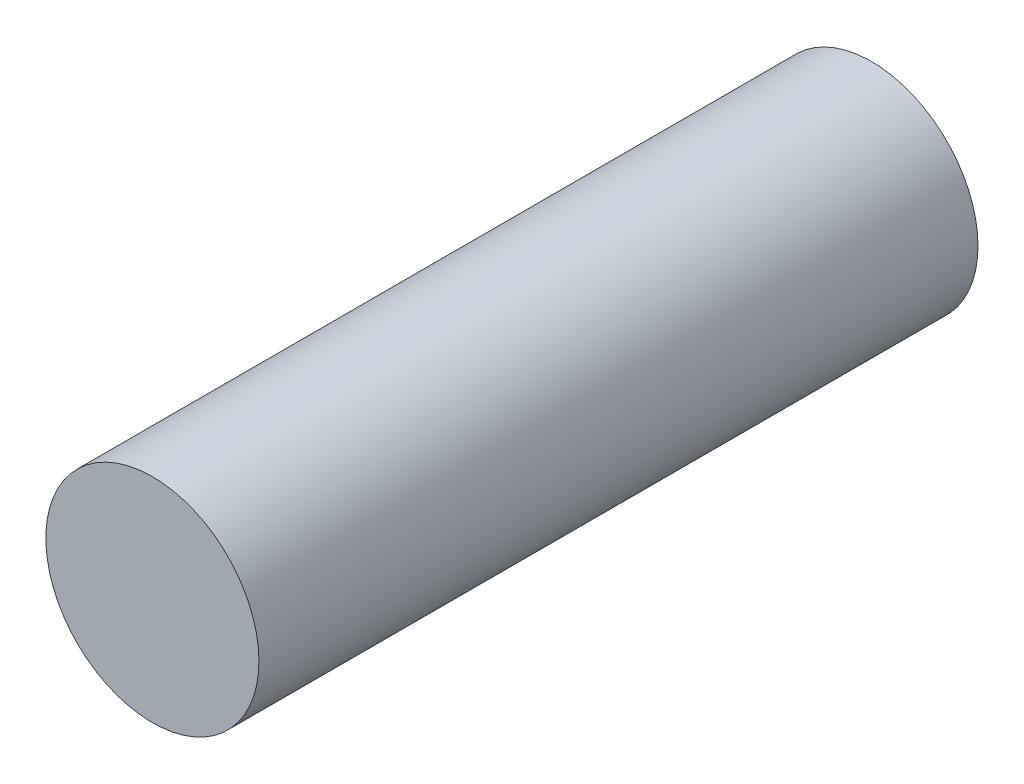
SolidWorks part; units mm, degrees
ref_plane "Front Plane" through (0, 0, 0) normal (0, 0, 1) x (1, 0, 0)
ref_plane "Top Plane" through (0, 0, 0) normal (0, 1, 0) x (1, 0, 0)
ref_plane "Right Plane" through (0, 0, 0) normal (1, 0, 0) x (0, 0, -1)
sketch "Sketch1" plane through (0, 0, 0) normal (0, 0, 1) x (1, 0, 0)
  circle A0 centre (0, 0) radius 4.445
  dimension "D1" = 8.89
extrude "L12_Shaft" add sketch "Sketch1" along normal blind 30
hole_wizard "Tap Drill for M8x1.25 Tap1" positions "Sketch3" profile "Sketch2" hole size "M8x1.25" standard "ANSI Metric"
sketch "Sketch3" plane through (0, 0, 0) normal (0, 0, -1) x (-1, 0, 0)
  point P0 (0, 0)
sketch "Sketch2" plane through (0, 0, 0) normal (1, 0, 0) x (0, 1, 0)
  line L0 (0, 0) -> (0, 11.5679)
  line L1 (0, 11.5679) -> (3.4, 9.525)
  line L2 (3.4, 9.525) -> (3.4, 0)
  line L5 (3.4, 0) -> (0, 0)
  line L10 (0, 11.5679) -> (-3.4, 9.525) construction
  line L11 (0, -6.35) -> (0, 107.95) construction
  dimension "Hole Dia." = 6.8
  dimension "Hole Depth" = 9.525
  dimension "Drill Angle" = 118
